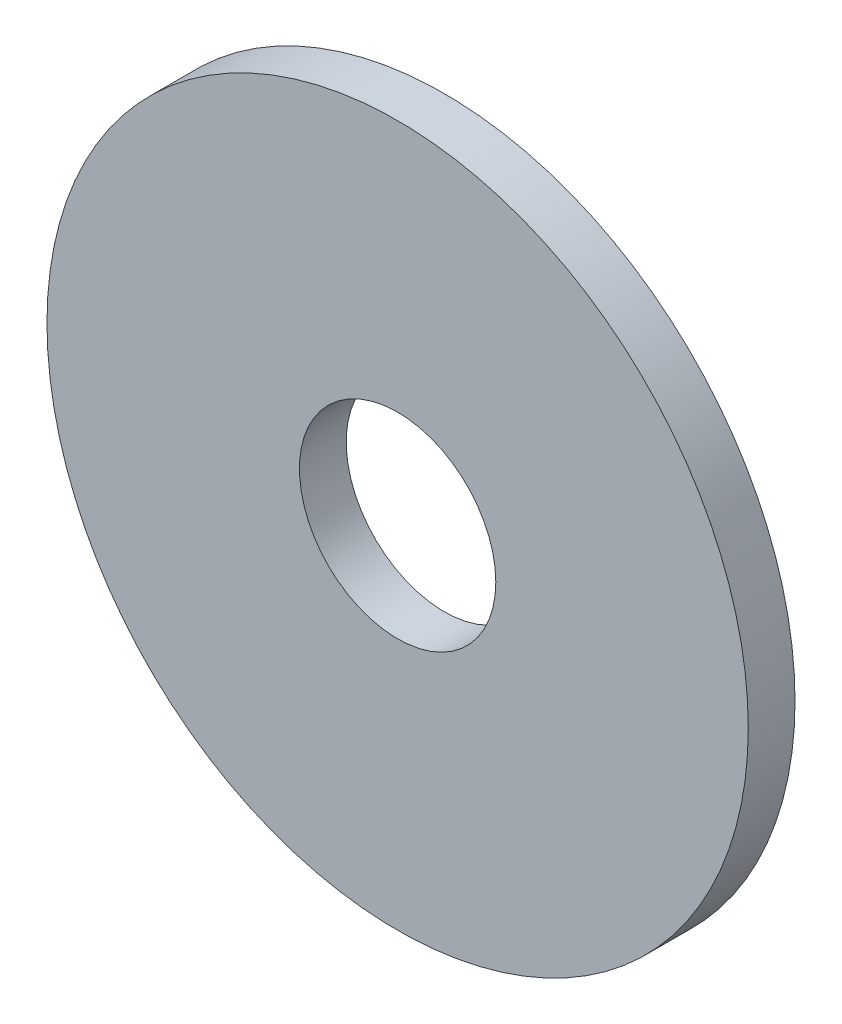
SolidWorks part; units mm, degrees
ref_plane "Piano frontale" through (0, 0, 0) normal (0, 0, 1) x (1, 0, 0)
ref_plane "Piano superiore" through (0, 0, 0) normal (0, 1, 0) x (1, 0, 0)
ref_plane "Piano destro" through (0, 0, 0) normal (1, 0, 0) x (0, 0, -1)
sketch "Schizzo1" plane through (0, 0, 0) normal (0, 0, 1) x (1, 0, 0)
  circle A0 centre (0, 0) radius 4.2
  circle A1 centre (0, 0) radius 15
  dimension "D1" = 30
  dimension "D2" = 8.4
extrude "Main body" add sketch "Schizzo1" along normal mid plane 2
